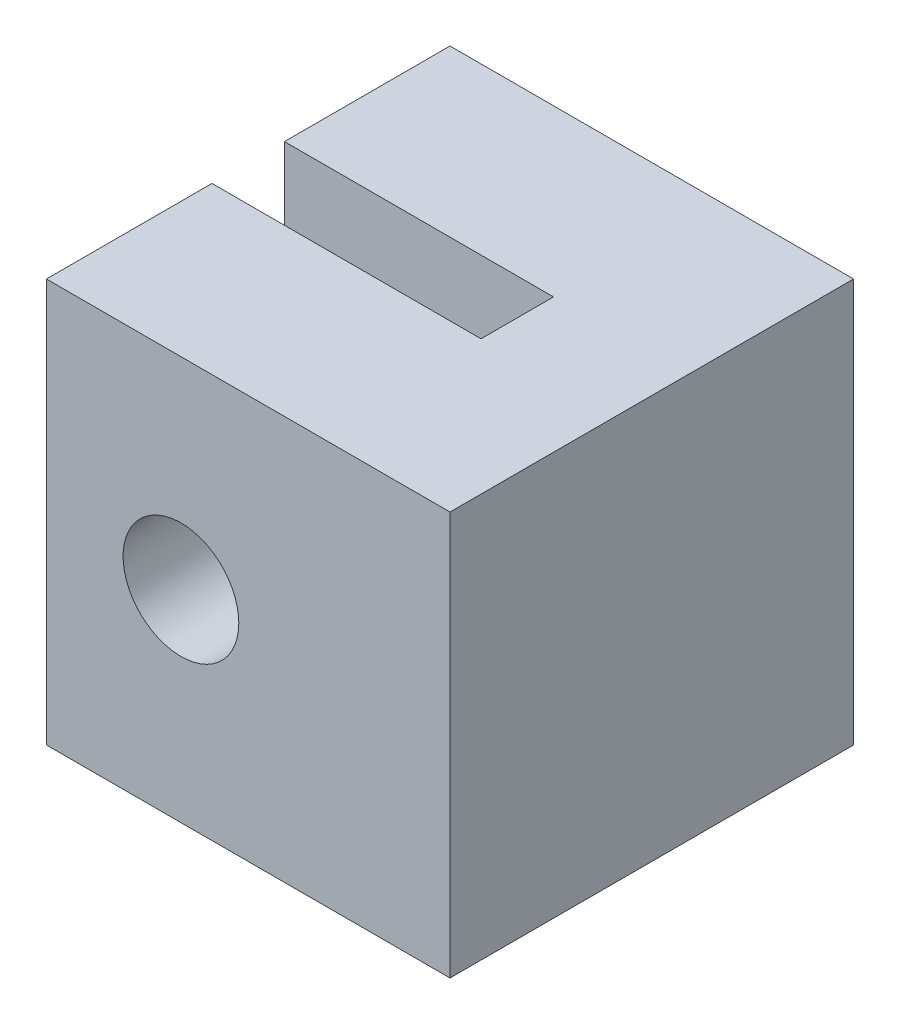
SolidWorks part; units mm, degrees
ref_plane "Ebene vorne" through (0, 0, 0) normal (0, 0, 1) x (1, 0, 0)
ref_plane "Ebene oben" through (0, 0, 0) normal (0, 1, 0) x (1, 0, 0)
ref_plane "Ebene rechts" through (0, 0, 0) normal (1, 0, 0) x (0, 0, -1)
sketch "Sketch1" plane through (0, 0, 0) normal (0, 0, 1) x (1, 0, 0)
  line L0 (0, 0) -> (0, -10.2134) construction
  line L1 (-7.5, 7.5) -> (7.5, 7.5)
  line L2 (-7.5, 7.5) -> (-7.5, -7.5)
  line L3 (-7.5, -7.5) -> (7.5, -7.5)
  line L4 (7.5, 7.5) -> (7.5, -7.5)
  line L5 (0, 0) -> (15.9756, 0) construction
  dimension "D1" = 15
  dimension "D2" = 15
extrude "Boss-Extrude1" add sketch "Sketch1" along normal blind 15
sketch "Sketch2" plane through (-7.5, 0, 0) normal (-1, 0, 0) x (0, 0, 1)
  line L0 (7.5, 7.5) -> (7.5, -7.5) construction
  line L1 (15, 7.5) -> (0, 7.5) construction
  line L2 (15, -7.5) -> (0, -7.5) construction
  line L4 (6.1529, 7.5) -> (8.8471, 7.5)
  line L5 (6.1529, 7.5) -> (6.1529, -7.5)
  line L6 (6.1529, -7.5) -> (8.8471, -7.5)
  line L7 (8.8471, 7.5) -> (8.8471, -7.5)
  dimension "D1" = 2.6943
extrude "Cut-Extrude1" cut sketch "Sketch2" against normal blind 10
sketch "Sketch3" plane through (0, 0, 15) normal (0, 0, 1) x (1, 0, 0)
  line L0 (-7.5, 0) -> (7.5, 0) construction
  line L1 (-7.5, 7.5) -> (-7.5, -7.5) construction
  line L2 (7.5, -7.5) -> (7.5, 7.5) construction
  line L3 (-2.5, 7.8386) -> (-2.5, -7.5) construction
  line L4 (-7.5, -7.5) -> (7.5, -7.5) construction
  circle A0 centre (-2.5, 0) radius 2.15
  dimension "D1" = 4.3
  dimension "D2" = 5
extrude "Cut-Extrude2" cut sketch "Sketch3" against normal blind 37 contours A0
